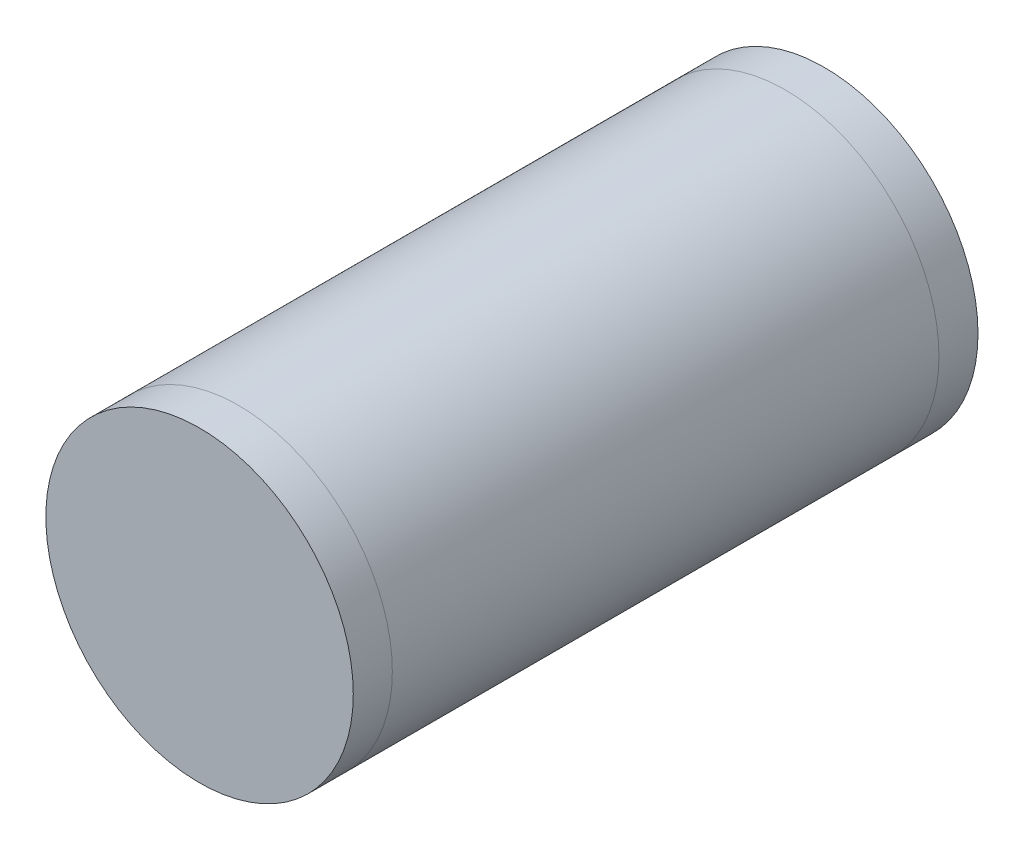
SolidWorks part; units mm, degrees
material "Acrylic (Medium-high impact)"
ref_plane "Front Plane" through (0, 0, 0) normal (0, 0, 1) x (1, 0, 0)
ref_plane "Top Plane" through (0, 0, 0) normal (0, 1, 0) x (1, 0, 0)
ref_plane "Right Plane" through (0, 0, 0) normal (1, 0, 0) x (0, 0, -1)
sketch "E-Housing Base Sketch" plane through (0, 0, 0) normal (0, 0, 1) x (1, 0, 0)
  circle A0 centre (0, 0) radius 50
  circle A1 centre (0, 0) radius 45
  dimension "D1" = 100
  dimension "D2" = 90
extrude "E-Housing Base" add sketch "E-Housing Base Sketch" along normal mid plane 177.8
sketch "Sketch3" plane through (0, 0, 88.9) normal (0, 0, 1) x (1, 0, 0)
  circle A0 centre (0, 0) radius 45
  circle A1 centre (0, 0) radius 50
extrude "End Cap 1" add sketch "Sketch3" along normal blind 12.7 separate body contours A1
sketch "End Cap Sketch" plane through (0, 0, -88.9) normal (0, 0, -1) x (-1, 0, 0)
  circle A0 centre (0, 0) radius 50
mirror "End Cap 2" about plane through (0, 0, 0) normal (0, 0, 1) of bodies 103
